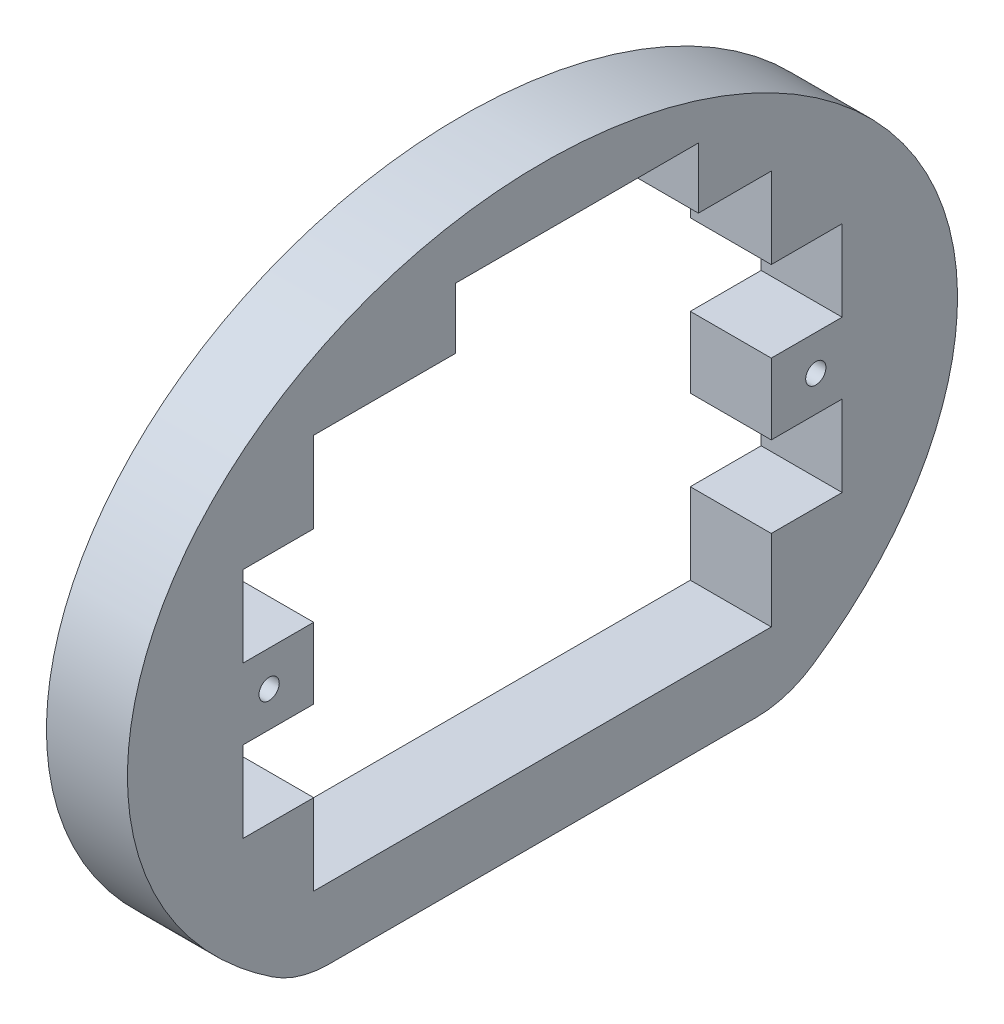
SolidWorks part; units mm, degrees
ref_plane "Piano frontale" through (0, 0, 0) normal (0, 0, 1) x (1, 0, 0)
ref_plane "Piano superiore" through (0, 0, 0) normal (0, 1, 0) x (1, 0, 0)
ref_plane "Piano destro" through (0, 0, 0) normal (1, 0, 0) x (0, 0, -1)
sketch "Schizzo1" plane through (0, 0, 0) normal (1, 0, 0) x (0, 0, -1)
  line L0 (-3.5, 15.5) -> (-3.5, 11.5)
  line L1 (-3.5, 11.5) -> (0, 11.5)
  line L2 (0, 11.5) -> (0, 8)
  line L3 (0, 8) -> (-3.5, 8)
  line L4 (-3.5, 8) -> (-3.5, 4)
  line L5 (-3.5, 4) -> (0, 4)
  line L6 (0, 4) -> (0, 0)
  line L7 (0, 0) -> (22.6, 0)
  line L8 (22.6, 0) -> (22.6, 4)
  line L9 (22.6, 4) -> (26.1, 4)
  line L10 (26.1, 4) -> (26.1, 8)
  line L11 (26.1, 8) -> (22.6, 8)
  line L12 (22.6, 8) -> (22.6, 11.5)
  line L13 (22.6, 11.5) -> (26.1, 11.5)
  line L14 (26.1, 11.5) -> (26.1, 15.5)
  line L15 (26.1, 15.5) -> (22.6, 15.5)
  line L16 (22.6, 15.5) -> (22.6, 19.5)
  line L17 (22.6, 19.5) -> (19, 19.5)
  line L18 (19, 19.5) -> (19, 22.5)
  line L19 (19, 22.5) -> (7, 22.5)
  line L20 (7, 22.5) -> (7, 19.5)
  line L21 (7, 19.5) -> (0, 19.5)
  line L22 (0, 19.5) -> (0, 15.5)
  line L23 (0, 15.5) -> (-3.5, 15.5)
  line L24 (-0.6507, -3.5) -> (23.2507, -3.5)
  circle A0 centre (-2.2, 9.75) radius 0.5
  circle A1 centre (24.8, 9.75) radius 0.5
  ellipse E0 centre (11.3, 9.5) end of major axis (31.8, 9.5) minor radius 16
  dimension "D18" = 1
  dimension "D20" = 1
  dimension "D1" = 22.6
  dimension "D2" = 4
  dimension "D3" = 4
  dimension "D4" = 11.5
  dimension "D5" = 4
  dimension "D6" = 4
  dimension "D7" = 3.5
  dimension "D8" = 3
  dimension "D9" = 12
  dimension "D10" = 7
  dimension "D11" = 3.5
  dimension "D12" = 20.5
  dimension "D13" = 16
  dimension "D14" = 11.3
  dimension "D15" = 13
  dimension "D16" = 13
  dimension "D17" = 2.2
  dimension "D19" = 1.75
  dimension "D21" = 1.75
  dimension "D22" = 2.2
extrude "Estrusione-Estrusione1" add sketch "Schizzo1" along normal blind 4 contours L24 E0 L23 L22 L21 L20 L19 L18 L17 L16 L15 L14 L13 L12 L11 L10 L9 L8 L7 L6 L5 L4 L3 L2 L1 L0
fillet "Raccordo1" radius 5 2 edges at (2, -3.5, 0.6507) (2, -3.5, -23.2507)
